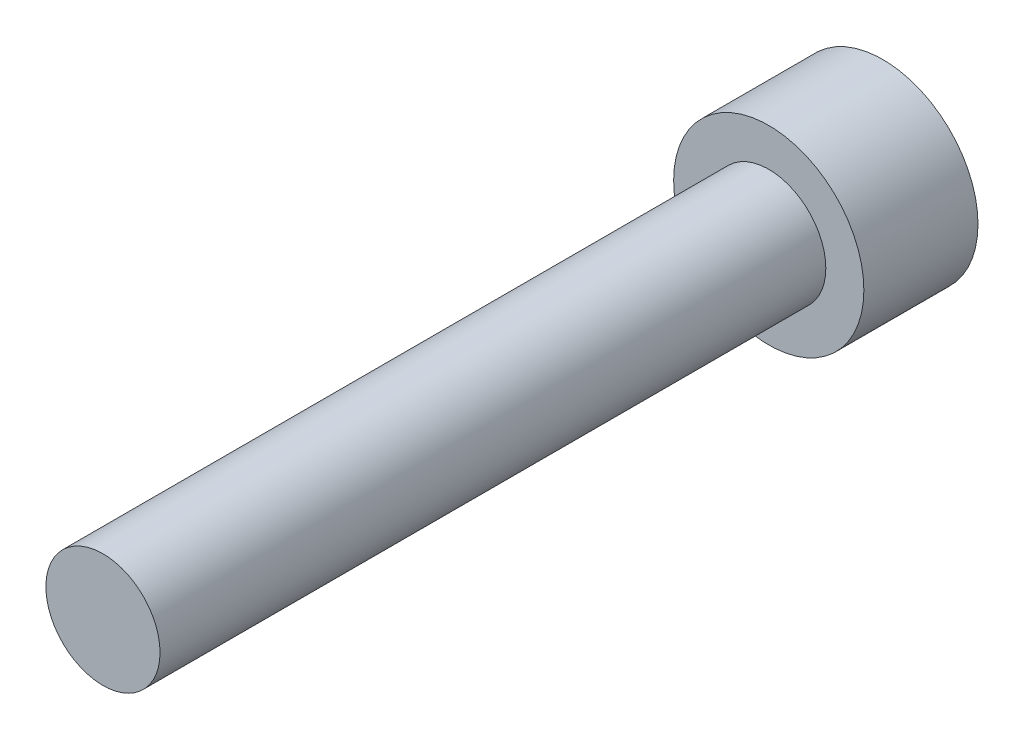
SolidWorks part; units mm, degrees
material "AISI 4340 Steel, normalized"
ref_plane "Front Plane" through (0, 0, 0) normal (0, 0, 1) x (1, 0, 0)
ref_plane "Top Plane" through (0, 0, 0) normal (0, 1, 0) x (1, 0, 0)
ref_plane "Right Plane" through (0, 0, 0) normal (1, 0, 0) x (0, 0, -1)
sketch "Sketch1" plane through (0, 0, 0) normal (0, 0, 1) x (1, 0, 0)
  circle A0 centre (0, 0) radius 5
extrude "Head_Envelope" add sketch "Sketch1" along normal blind 6 from offset 6
sketch "Sketch2" plane through (0, 0, 0) normal (0, 0, 1) x (1, 0, 0)
  circle A0 centre (0, 0) radius 3
extrude "Thread_Major_Envelope" add sketch "Sketch2" along normal blind 35
